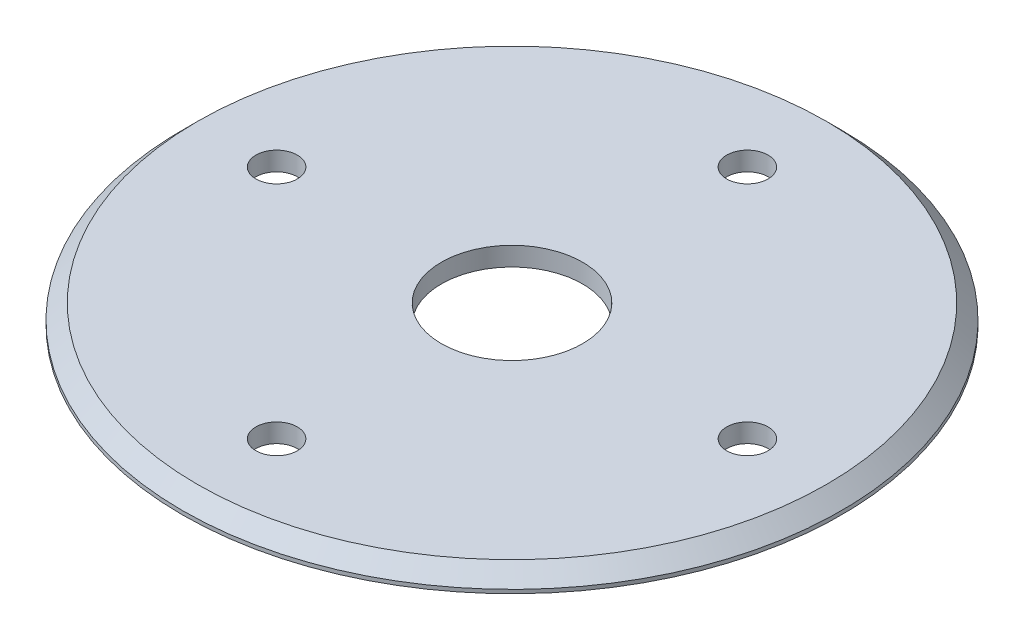
SolidWorks part; units mm, degrees
ref_plane "Front Plane" through (0, 0, 0) normal (0, 0, 1) x (1, 0, 0)
ref_plane "Top Plane" through (0, 0, 0) normal (0, 1, 0) x (1, 0, 0)
ref_plane "Right Plane" through (0, 0, 0) normal (1, 0, 0) x (0, 0, -1)
sketch "Sketch1" plane through (0, 0, 0) normal (0, 1, 0) x (1, 0, 0)
  circle A0 centre (0, 0) radius 35
  circle A1 centre (0, 25) radius 2.2
  circle A2 centre (25, 0) radius 2.2
  circle A3 centre (0, -25) radius 2.2
  circle A4 centre (-25, 0) radius 2.2
  circle A5 centre (0, 0) radius 7.5
  point P14 (0, 0)
  dimension "D1" = 70
  dimension "D2" = 4.4
  dimension "D5" = 15
  dimension "D3" = 25
  dimension "D4" = 4
extrude "Boss-Extrude1" add sketch "Sketch1" along normal blind 2
chamfer "Chamfer1" distance 1.6 angle 45 1 edges at (0, 2, 35)
